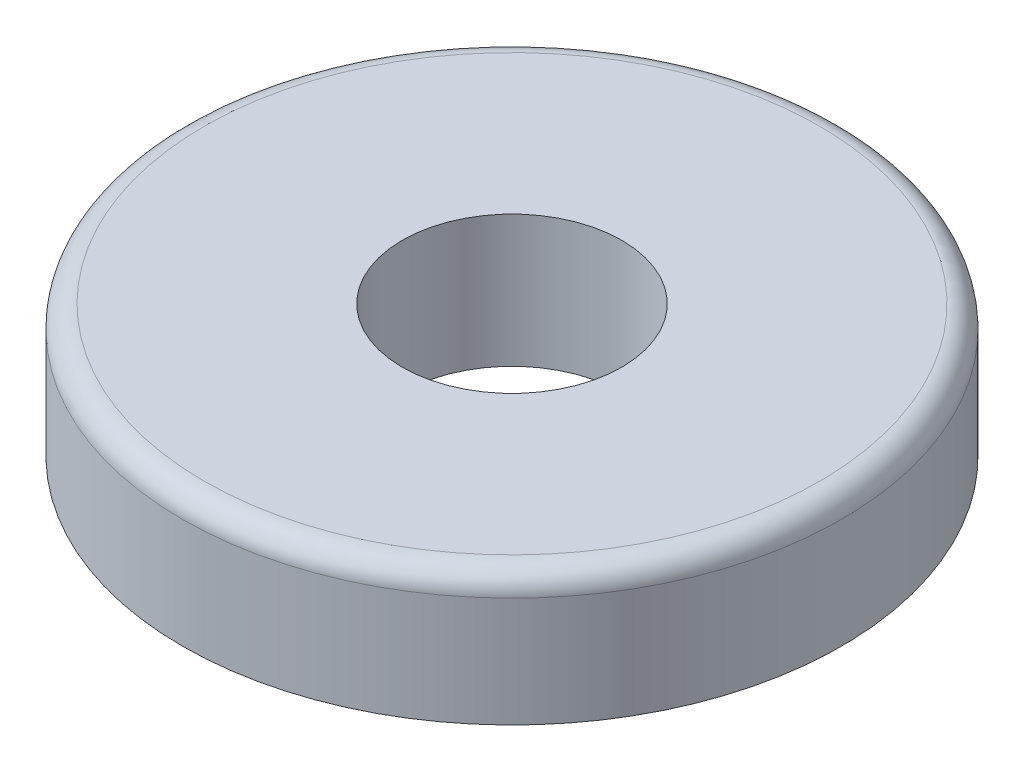
SolidWorks part; units mm, degrees
ref_plane "Plan de face" through (0, 0, 0) normal (0, 0, 1) x (1, 0, 0)
ref_plane "Plan de dessus" through (0, 0, 0) normal (0, 1, 0) x (1, 0, 0)
ref_plane "Plan de droite" through (0, 0, 0) normal (1, 0, 0) x (0, 0, -1)
sketch "Esquisse2" plane through (0, 0, 0) normal (0, 1, 0) x (1, 0, 0)
  circle A0 centre (0, 0) radius 1.25
  circle A1 centre (0, 0) radius 3.75
  dimension "D1" = 7.5
  dimension "D2" = 2.5
extrude "Boss.-Extru.1" add sketch "Esquisse2" along normal blind 1.5
fillet "Congé2" radius 0.25 1 edges at (0, 1.5, 3.75)
